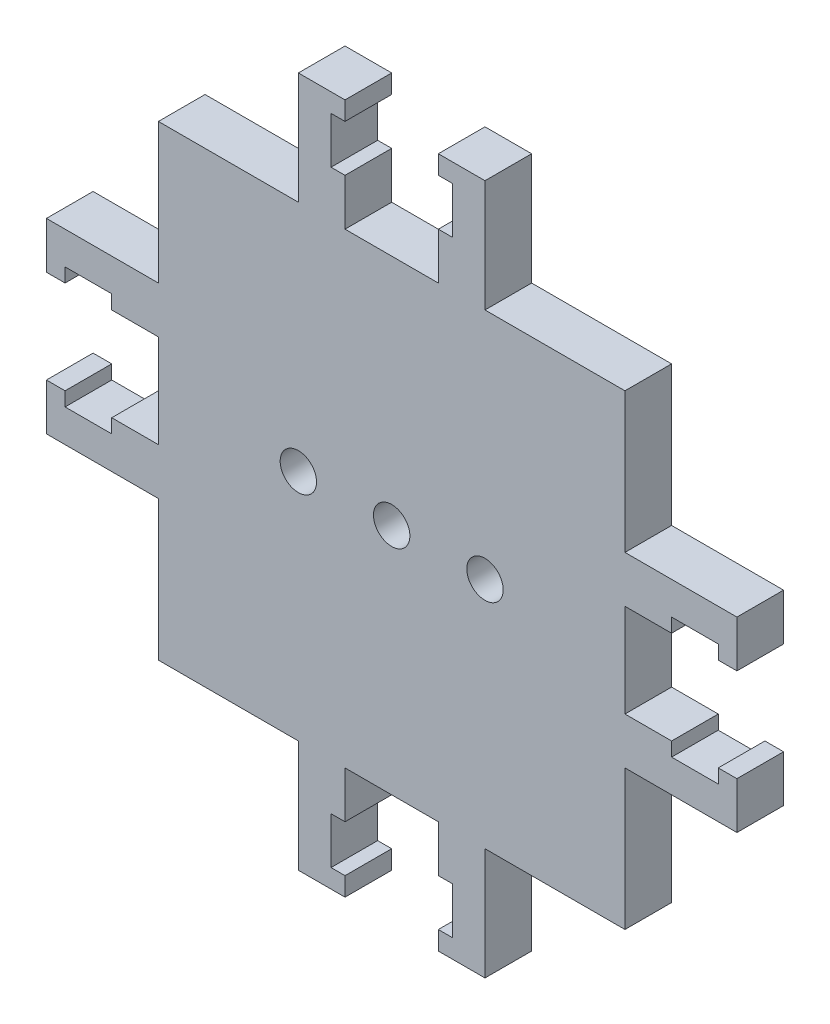
SolidWorks part; units mm, degrees
ref_plane "Plan de face" through (0, 0, 0) normal (0, 0, 1) x (1, 0, 0)
ref_plane "Plan de dessus" through (0, 0, 0) normal (0, 1, 0) x (1, 0, 0)
ref_plane "Plan de droite" through (0, 0, 0) normal (1, 0, 0) x (0, 0, -1)
sketch "Esquisse1" plane through (0, 0, 0) normal (0, 0, 1) x (1, 0, 0)
  line L0 (0, -10.9037) -> (0, 0) construction
  line L1 (0, 0) -> (78.1485, 0) construction
  line L2 (-25, 25) -> (-10, 25)
  line L3 (0, 0) -> (90.4553, 90.4553) construction
  line L4 (10, 25) -> (25, 25)
  line L5 (-25, -25) -> (-10, -25)
  line L6 (25, -25) -> (25, -10)
  line L8 (25, 10) -> (25, 25)
  line L9 (-25, -25) -> (-25, -10)
  line L10 (-25, 10) -> (-25, 25)
  line L13 (10, -25) -> (25, -25)
  circle A0 centre (0, 0) radius 1.95
  circle A1 centre (10, 0) radius 1.95
  circle A2 centre (-10, 0) radius 1.95
  point P16 (0, 0)
  line B0 (0, -25) -> (0, -13.135) construction
  line B1 (0, -25) -> (-5, -25)
  line B2 (-5, -30) -> (-10, -30) construction
  line B3 (-10, -30) -> (-10, -25)
  line B4 (-5, -30) -> (-5, -25)
  line B5 (0, -25) -> (5, -25)
  line B6 (5, -25) -> (5, -30)
  line B7 (5, -30) -> (10, -30) construction
  line B8 (10, -30) -> (10, -25)
  line B9 (-10, -30) -> (-10, -37)
  line B10 (-10, -37) -> (-5, -37)
  line B11 (-5, -37) -> (-5, -35)
  line B12 (-5, -35) -> (-6.5, -35)
  line B13 (-6.5, -35) -> (-6.5, -30)
  line B14 (-6.5, -30) -> (-5, -30)
  line B15 (5, -35) -> (6.5, -35)
  line B16 (10, -37) -> (5, -37)
  line B17 (5, -37) -> (5, -35)
  line B18 (6.5, -35) -> (6.5, -30)
  line B19 (10, -30) -> (10, -37)
  line B20 (10, -30) -> (10, -25)
  line B21 (5, -30) -> (6.5, -30)
  line B22 (0, -25) -> (0, -13.135) construction
  line B23 (0, -25) -> (5, -25)
  line B24 (5, -30) -> (10, -30) construction
  line B25 (10, -30) -> (10, -25)
  line B26 (5, -30) -> (5, -25)
  line B27 (0, -25) -> (-5, -25)
  line B28 (-5, -25) -> (-5, -30)
  line B29 (-5, -30) -> (-10, -30) construction
  line B30 (-10, -30) -> (-10, -25)
  line B31 (10, -30) -> (10, -37)
  line B32 (10, -37) -> (5, -37)
  line B33 (5, -37) -> (5, -35)
  line B34 (5, -35) -> (6.5, -35)
  line B35 (6.5, -35) -> (6.5, -30)
  line B36 (6.5, -30) -> (5, -30)
  line B37 (-5, -35) -> (-6.5, -35)
  line B38 (-10, -37) -> (-5, -37)
  line B39 (-5, -37) -> (-5, -35)
  line B40 (-6.5, -35) -> (-6.5, -30)
  line B41 (-10, -30) -> (-10, -37)
  line B42 (-10, -30) -> (-10, -25)
  line B43 (-5, -30) -> (-6.5, -30)
  line B44 (0, 25) -> (0, 13.135) construction
  line B45 (0, 25) -> (-5, 25)
  line B46 (-5, 30) -> (-10, 30) construction
  line B47 (-10, 30) -> (-10, 25)
  line B48 (-5, 30) -> (-5, 25)
  line B49 (0, 25) -> (5, 25)
  line B50 (5, 25) -> (5, 30)
  line B51 (5, 30) -> (10, 30) construction
  line B52 (10, 30) -> (10, 25)
  line B53 (-10, 30) -> (-10, 37)
  line B54 (-10, 37) -> (-5, 37)
  line B55 (-5, 37) -> (-5, 35)
  line B56 (-5, 35) -> (-6.5, 35)
  line B57 (-6.5, 35) -> (-6.5, 30)
  line B58 (-6.5, 30) -> (-5, 30)
  line B59 (5, 35) -> (6.5, 35)
  line B60 (10, 37) -> (5, 37)
  line B61 (5, 37) -> (5, 35)
  line B62 (6.5, 35) -> (6.5, 30)
  line B63 (10, 30) -> (10, 37)
  line B64 (10, 30) -> (10, 25)
  line B65 (5, 30) -> (6.5, 30)
  line B66 (25, 0) -> (13.135, 0) construction
  line B67 (25, 0) -> (25, -5)
  line B68 (30, -5) -> (30, -10) construction
  line B69 (30, -10) -> (25, -10)
  line B70 (30, -5) -> (25, -5)
  line B71 (25, 0) -> (25, 5)
  line B72 (25, 5) -> (30, 5)
  line B73 (30, 5) -> (30, 10) construction
  line B74 (30, 10) -> (25, 10)
  line B75 (30, -10) -> (37, -10)
  line B76 (37, -10) -> (37, -5)
  line B77 (37, -5) -> (35, -5)
  line B78 (35, -5) -> (35, -6.5)
  line B79 (35, -6.5) -> (30, -6.5)
  line B80 (30, -6.5) -> (30, -5)
  line B81 (35, 5) -> (35, 6.5)
  line B82 (37, 10) -> (37, 5)
  line B83 (37, 5) -> (35, 5)
  line B84 (35, 6.5) -> (30, 6.5)
  line B85 (30, 10) -> (37, 10)
  line B86 (30, 10) -> (25, 10)
  line B87 (30, 5) -> (30, 6.5)
  line B88 (-25, 0) -> (-13.135, 0) construction
  line B89 (-25, 0) -> (-25, -5)
  line B90 (-30, -5) -> (-30, -10) construction
  line B91 (-30, -10) -> (-25, -10)
  line B92 (-30, -5) -> (-25, -5)
  line B93 (-25, 0) -> (-25, 5)
  line B94 (-25, 5) -> (-30, 5)
  line B95 (-30, 5) -> (-30, 10) construction
  line B96 (-30, 10) -> (-25, 10)
  line B97 (-30, -10) -> (-37, -10)
  line B98 (-37, -10) -> (-37, -5)
  line B99 (-37, -5) -> (-35, -5)
  line B100 (-35, -5) -> (-35, -6.5)
  line B101 (-35, -6.5) -> (-30, -6.5)
  line B102 (-30, -6.5) -> (-30, -5)
  line B103 (-35, 5) -> (-35, 6.5)
  line B104 (-37, 10) -> (-37, 5)
  line B105 (-37, 5) -> (-35, 5)
  line B106 (-35, 6.5) -> (-30, 6.5)
  line B107 (-30, 10) -> (-37, 10)
  line B108 (-30, 10) -> (-25, 10)
  line B109 (-30, 5) -> (-30, 6.5)
  dimension "D11" = 3.9
  dimension "D4" = 3.9
  dimension "D2" = 50
  dimension "D3" = 50
  dimension "D5" = 45
  dimension "D6" = 10
sketch_block_instance "Insert plots ep 5mm avec ergots-1"
sketch_block "Insert plots ep 5mm avec ergots" parameters "D1"=10, "D2"=5, "D3"=5, "D4"=5, "D5"=2, "D6"=1.5, "D7"=2, "D8"=2, "D9"=2.0716, "D10"=2
sketch_block_instance "Insert plots ep 5mm avec ergots-3"
sketch_block_instance "Insert plots ep 5mm avec ergots-4"
sketch_block_instance "Insert plots ep 5mm avec ergots-6"
sketch_block_instance "Insert plots ep 5mm avec ergots-7"
extrude "Boss.-Extru.1" add sketch "Esquisse1" along normal blind 5
